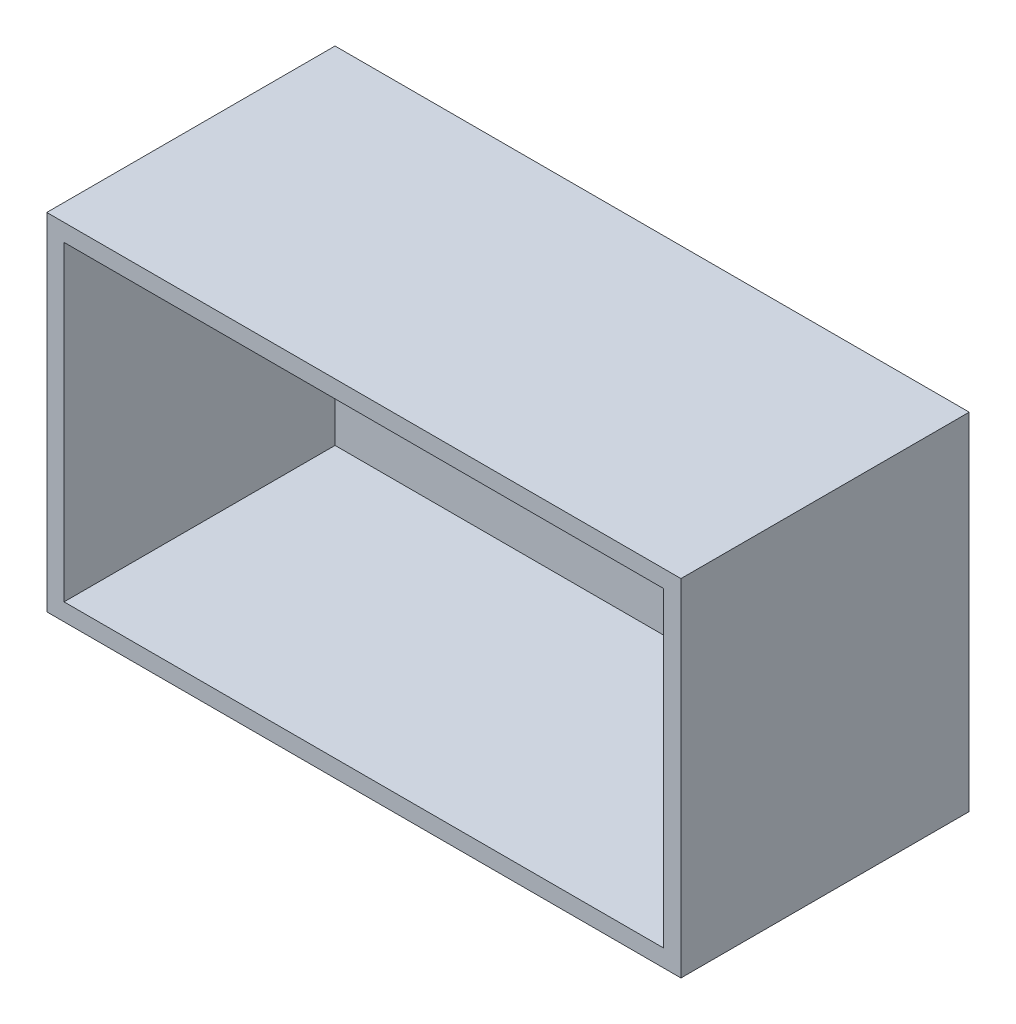
SolidWorks part; units mm, degrees
ref_plane "정면" through (0, 0, 0) normal (0, 0, 1) x (1, 0, 0)
ref_plane "윗면" through (0, 0, 0) normal (0, 1, 0) x (1, 0, 0)
ref_plane "우측면" through (0, 0, 0) normal (1, 0, 0) x (0, 0, -1)
sketch "스케치1" plane through (0, 0, 0) normal (0, 0, 1) x (1, 0, 0)
  line L1 (-55, -30) -> (55, -30)
  line L2 (-55, -30) -> (-55, 30)
  line L3 (-55, 30) -> (55, 30)
  line L4 (55, -30) -> (55, 30)
  line L5 (-55, -30) -> (55, 30) construction
  line L6 (-55, 30) -> (55, -30) construction
  point P0 (0, 0)
  dimension "D1" = 110
  dimension "D2" = 60
extrude "보스-돌출2" add sketch "스케치1" along normal blind 3
sketch "스케치2" plane through (0, 0, 3) normal (0, 0, 1) x (1, 0, 0)
  line L1 (-55, -30) -> (55, -30)
  line L2 (-55, -30) -> (-55, 30)
  line L3 (-55, 30) -> (55, 30)
  line L4 (55, -30) -> (55, 30)
  line L5 (-55, -30) -> (55, 30) construction
  line L6 (-55, 30) -> (55, -30) construction
  point P0 (0, 0)
extrude "돌출-얇게2" add sketch "스케치2" along normal blind 47 thin thin type one direction reverse wall 3
